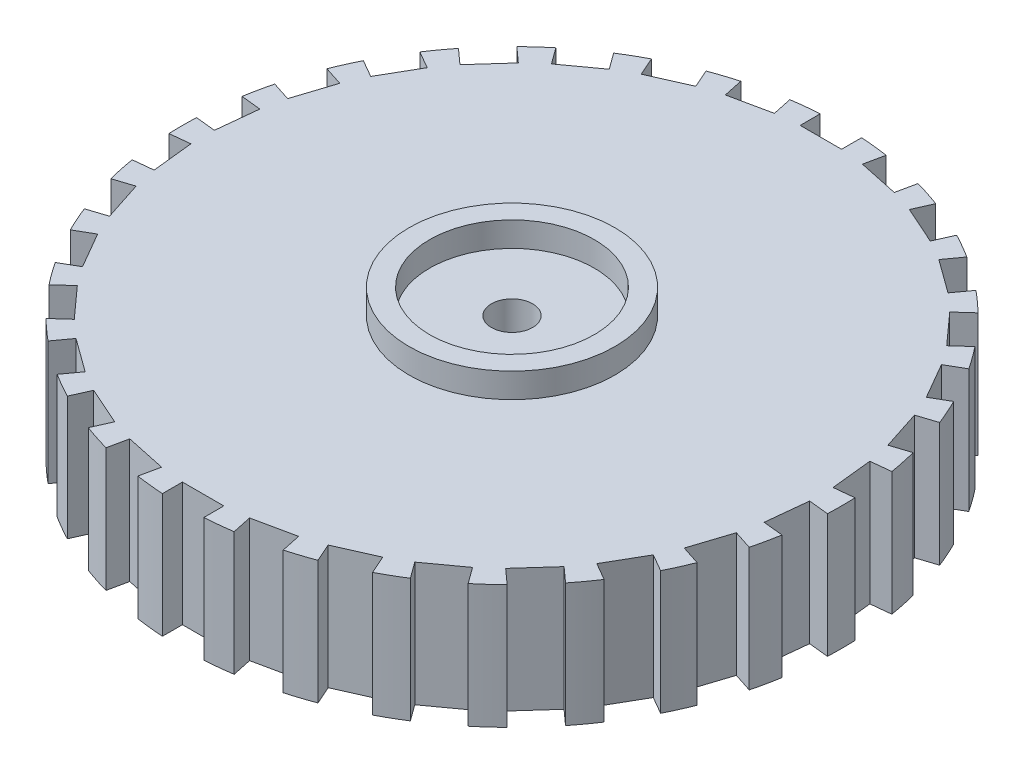
SolidWorks part; units mm, degrees
ref_plane "Alzado" through (0, 0, 0) normal (0, 0, 1) x (1, 0, 0)
ref_plane "Planta" through (0, 0, 0) normal (0, 1, 0) x (1, 0, 0)
ref_plane "Vista lateral" through (0, 0, 0) normal (1, 0, 0) x (0, 0, -1)
sketch "Croquis1" plane through (0, 0, 0) normal (0, 1, 0) x (1, 0, 0)
  circle A0 centre (0, 0) radius 40
extrude "Saliente-Extruir1" add sketch "Croquis1" along normal blind 15
sketch "Croquis2" plane through (0, 0, 0) normal (0, 1, 0) x (1, 0, 0)
  line L1 (-2.5105, 42.5083) -> (2.5105, 42.5083)
  line L2 (-2.5105, 42.5083) -> (-2.5105, 37.4917)
  line L3 (-2.5105, 37.4917) -> (2.5105, 37.4917)
  line L4 (2.5105, 42.5083) -> (2.5105, 37.4917)
  line L5 (-2.5105, 42.5083) -> (2.5105, 37.4917) construction
  line L6 (-2.5105, 37.4917) -> (2.5105, 42.5083) construction
  circle A0 centre (0, 0) radius 40 construction
  point P0 (0, 40)
extrude "Cortar-Extruir1" cut sketch "Croquis2" along normal blind 52 and the other way blind 16
pattern_circular "MatrizC1" count 30 over 360 about axis through (0, 0, 0) along (0, 1, 0) of "Cortar-Extruir1"
sketch "Croquis3" plane through (0, 0, 0) normal (0, 1, 0) x (1, 0, 0)
  circle A0 centre (0, 0) radius 12.5
  circle A1 centre (0, 0) radius 10
extrude "Saliente-Extruir2" add sketch "Croquis3" along normal blind 18 and the other way blind 3
sketch "Croquis4" plane through (0, 0, 0) normal (0, 1, 0) x (1, 0, 0)
  circle A0 centre (0, 0) radius 2.5
extrude "Cortar-Extruir2" cut sketch "Croquis4" along normal blind 60 and the other way blind 27
